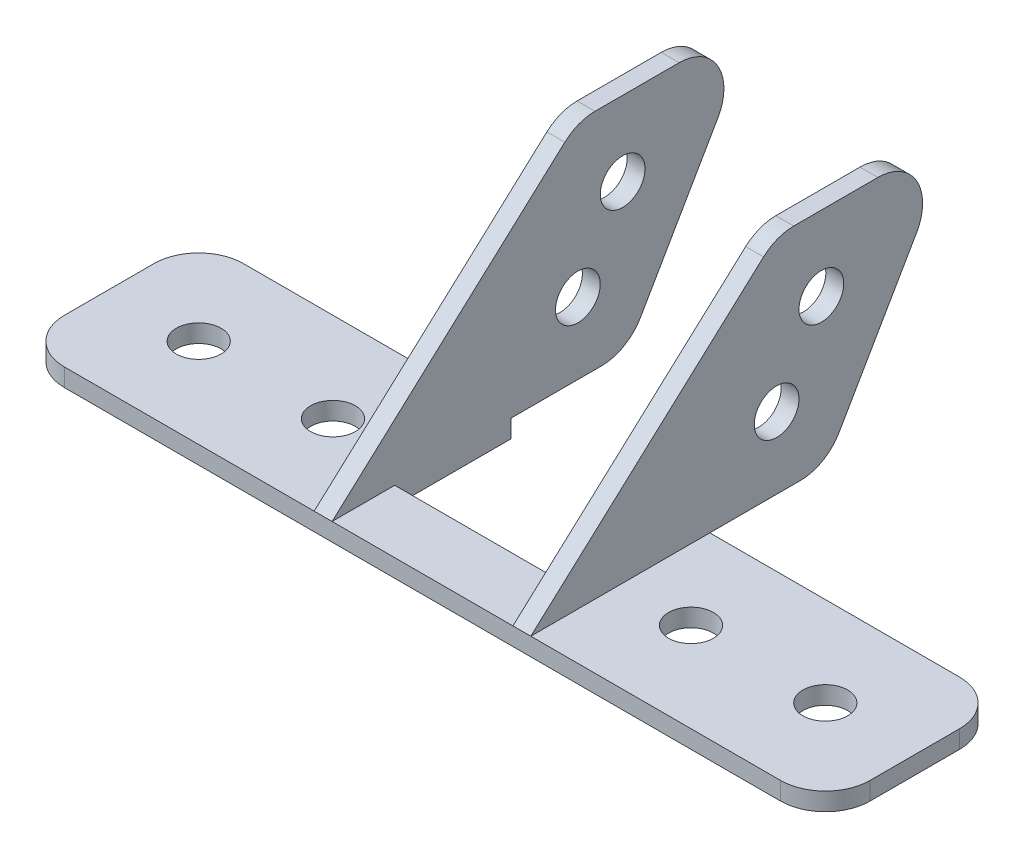
SolidWorks part; units mm, degrees
material "AISI 304"
ref_plane "Front Plane" through (0, 0, 0) normal (0, 0, 1) x (1, 0, 0)
ref_plane "Top Plane" through (0, 0, 0) normal (0, 1, 0) x (1, 0, 0)
ref_plane "Right Plane" through (0, 0, 0) normal (1, 0, 0) x (0, 0, -1)
sketch "Sketch1" plane through (0, 0, 0) normal (0, 1, 0) x (1, 0, 0)
  line L0 (0, 36.0085) -> (0, -31.321) construction
  line L1 (-51.4773, 0) -> (55.0568, 0) construction
  line L2 (-10.1, 10) -> (-10.1, 0)
  line L3 (-45, 10) -> (-10.1, 10)
  line L4 (-45, 10) -> (-45, -10)
  line L5 (-45, -10) -> (45, -10)
  line L6 (45, 10) -> (45, -10)
  line L7 (-45, 10) -> (45, -10) construction
  line L8 (-45, -10) -> (45, 10) construction
  line L9 (10.1, 10) -> (10.1, 0)
  line L11 (-10.1, 36.0085) -> (-10.1, -31.321) construction
  line L12 (10.1, 36.0085) -> (10.1, -31.321) construction
  line L13 (10.1, 10) -> (45, 10)
  line L14 (-10.1, 0) -> (-10.1, -3)
  line L15 (-10.1, -3) -> (10.1, -3)
  line L16 (10.1, -3) -> (10.1, 0)
  point P6 (0, 0)
  dimension "D1" = 90
  dimension "D2" = 20
  dimension "D5" = 3
  dimension "D3" = 10.1
  dimension "D4" = 10.1
extrude "Boss-Extrude1" add sketch "Sketch1" along normal blind 2
sketch "Sketch2" plane through (0, 2, 0) normal (0, 1, 0) x (1, 0, 0)
  line L0 (0, 21.9629) -> (0, -24.4623) construction
  line L1 (-55.3603, 0) -> (56.2351, 0) construction
  circle A0 centre (-20, 0) radius 2.5
  circle A1 centre (-35, 0) radius 2.5
  circle A2 centre (20, 0) radius 2.5
  circle A3 centre (35, 0) radius 2.5
  dimension "D1" = 5
  dimension "D2" = 5
  dimension "D3" = 20
  dimension "D4" = 15
extrude "Cut-Extrude1" cut sketch "Sketch2" against normal through all
sketch "Sketch3" plane through (10.1, 0, 0) normal (-1, 0, 0) x (0, 0, 1)
  line L0 (10, 2) -> (-17.4338, 27)
  line L1 (-17.4338, 27) -> (-37.4338, 27)
  line L2 (-37.4338, 27) -> (-23, 2)
  line L3 (-23, 2) -> (10, 2)
  point P3 (-19.5654, 2)
  point P6 (0, 0)
  point P7 (-41.3095, 39.7355)
  dimension "D1" = 120
  dimension "D2" = 33
  dimension "D3" = 25
  dimension "D4" = 20
extrude "Boss-Extrude2" add sketch "Sketch3" against normal blind 2 contours L3 L0 L1 L2
sketch "Sketch4" plane through (12.1, 0, 0) normal (1, 0, 0) x (0, 0, -1)
  line L0 (10, 2) -> (-10, 2) construction
  circle A0 centre (22.46, 18.65) radius 2.5
  circle A1 centre (17.46, 9.99) radius 2.5
  dimension "D1" = 5
  dimension "D4" = 5
  dimension "D2" = 12.46
  dimension "D3" = 16.65
  dimension "D5" = 7.46
  dimension "D6" = 7.99
extrude "Cut-Extrude2" cut sketch "Sketch4" against normal through all
sketch "Sketch5" plane through (-10.1, 0, 0) normal (1, 0, 0) x (0, 0, -1)
  line L0 (-10, 2) -> (17.4338, 27)
  line L1 (17.4338, 27) -> (37.4338, 27)
  line L2 (37.4338, 27) -> (23, 2)
  line L3 (23, 2) -> (-10, 2)
  circle A0 centre (22.46, 18.65) radius 2.5
  circle A1 centre (17.46, 9.99) radius 2.5
  dimension "D1" = 5
  dimension "D2" = 5
extrude "Boss-Extrude3" add sketch "Sketch5" against normal blind 2
fillet "Fillet1" radius 5 6 edges at (11.1, 2, -23) (-11.1, 2, -23) (-11.1, 27, -17.4338) (11.1, 27, -17.4338) (-11.1, 27, -37.4338) (11.1, 27, -37.4338)
fillet "Fillet2" radius 5 4 edges at (45, 1, -10) (45, 1, 10) (-45, 1, 10) (-45, 1, -10)
